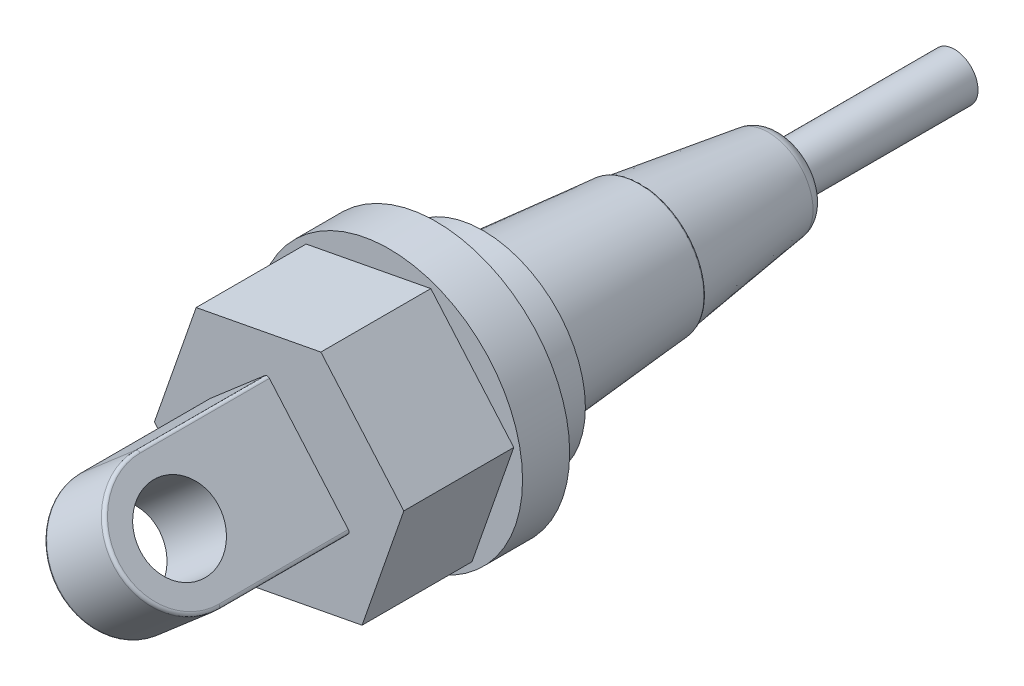
SolidWorks part; units mm, degrees
ref_plane "前视基准面" through (0, 0, 0) normal (0, 0, 1) x (1, 0, 0)
ref_plane "上视基准面" through (0, 0, 0) normal (0, 1, 0) x (1, 0, 0)
ref_plane "右视基准面" through (0, 0, 0) normal (1, 0, 0) x (0, 0, -1)
sketch "草图1" plane through (0, 0, 0) normal (0, 0, 1) x (1, 0, 0)
  circle A0 centre (0, 6.2822) radius 8.5
  dimension "D1" = 17
extrude "凸台-拉伸1" add sketch "草图1" along normal blind 3
sketch "草图2" plane through (0, 0, 3) normal (0, 0, 1) x (1, 0, 0)
  line L1 (5.2814, 0.1633) -> (7.9398, 7.7966)
  line L2 (7.9398, 7.7966) -> (2.6584, 13.9154)
  line L3 (2.6584, 13.9154) -> (-5.2814, 12.401)
  line L4 (-5.2814, 12.401) -> (-7.9398, 4.7678)
  line L5 (-7.9398, 4.7678) -> (-2.6584, -1.3511)
  line L6 (-2.6584, -1.3511) -> (5.2814, 0.1633)
  circle A0 centre (0, 6.2822) radius 7 construction
  dimension "D1" = 14
extrude "凸台-拉伸2" add sketch "草图2" along normal blind 7
sketch "草图3" plane through (0, 0, 0) normal (0, 0, -1) x (-1, 0, 0)
  circle A0 centre (0, 6.2822) radius 6.5
  dimension "D1" = 13
extrude "凸台-拉伸3" add sketch "草图3" along normal blind 3
sketch "草图4" plane through (0, 0, -3) normal (0, 0, -1) x (-1, 0, 0)
  circle A0 centre (0, 6.2822) radius 5
  dimension "D1" = 10
extrude "凸台-拉伸4" add sketch "草图4" along normal blind 10 draft 5
sketch "草图5" plane through (0, 0, -13) normal (0, 0, -1) x (-1, 0, 0)
  circle A0 centre (0, 6.2822) radius 4
  dimension "D1" = 8
extrude "凸台-拉伸5" add sketch "草图5" along normal blind 9 draft 8
fillet "圆角1" radius 0.1 1 edges at (-4.1251, 6.2822, -13)
fillet "圆角2" radius 1 1 edges at (-2.7351, 6.2822, -22)
ref_plane "基准面1" through (3.1074, 2.6821, 0) normal (-0.757, -0.6534, 0) x (0, 0, 1)
sketch "草图7" plane through (3.1074, 2.6821, 0) normal (-0.757, -0.6534, 0) x (0, 0, 1)
  line L0 (10, 8.7971) -> (18.2315, 8.7971)
  line L1 (18.2315, 0.7142) -> (10, 0.7142)
  line L2 (10, 8.7971) -> (10, 0.7142)
  arc A0 (18.2315, 8.7971) -> (18.2315, 0.7142) centre (18.2315, 4.7557) cw
  circle A1 centre (18.2315, 4.7557) radius 2.5
  dimension "D1" = 5
extrude "凸台-拉伸6" add sketch "草图7" along normal mid plane 5
fillet "圆角3" radius 0.2 6 edges at (4.5332, 4.8563, 14.1158) (-0.7482, 10.9751, 14.1158) (0.7482, 1.5892, 14.1158) (-4.5332, 7.7081, 14.1158) (1.8925, 7.9157, 22.273) (-1.8925, 4.6487, 22.273)
sketch "草图8" plane through (0, 0, -22) normal (0, 0, -1) x (-1, 0, 0)
  circle A0 centre (0, 6.2822) radius 1.5
  dimension "D1" = 3
extrude "凸台-拉伸7" add sketch "草图8" along normal blind 11
